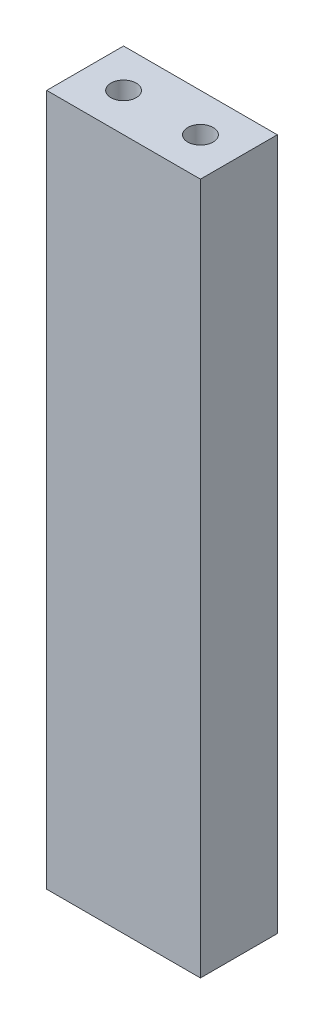
SolidWorks part; units mm, degrees
ref_plane "Front Plane" through (0, 0, 0) normal (0, 0, 1) x (1, 0, 0)
ref_plane "Top Plane" through (0, 0, 0) normal (0, 1, 0) x (1, 0, 0)
ref_plane "Right Plane" through (0, 0, 0) normal (1, 0, 0) x (0, 0, -1)
sketch "Sketch1" plane through (0, 0, 0) normal (0, 1, 0) x (1, 0, 0)
  line L1 (-10, -5) -> (10, -5)
  line L2 (-10, -5) -> (-10, 5)
  line L3 (-10, 5) -> (10, 5)
  line L4 (10, -5) -> (10, 5)
  line L5 (-10, -5) -> (10, 5) construction
  line L6 (-10, 5) -> (10, -5) construction
  point P0 (0, 0)
  dimension "D1" = 20
  dimension "D2" = 10
extrude "Boss-Extrude1" add sketch "Sketch1" along normal blind 90
hole_wizard "M4x0.7 Tapped Hole1" positions "Sketch2" profile "Sketch4" tap size "M4x0.7" standard "ANSI Metric"
sketch "Sketch2" plane through (0, 0, 0) normal (0, -1, 0) x (-1, 0, 0)
  line L0 (-5, 0) -> (5, 0)
  point P1 (-5, 0)
  point P2 (5, 0)
  point P4 (0, 0)
  dimension "D1" = 10
sketch "Sketch4" plane through (5, 0, 0) normal (1, 0, 0) x (0, 0, -1)
  line L0 (0, 0) -> (0, 15.9914)
  line L1 (0, 15.9914) -> (1.65, 15)
  line L2 (1.65, 15) -> (1.65, 0)
  line L5 (1.65, 0) -> (0, 0)
  line L10 (0, 15.9914) -> (-1.65, 15) construction
  line L11 (0, -6.35) -> (0, 107.95) construction
  dimension "Tap Drill Dia." = 3.3
  dimension "Tap Drill Depth" = 15
  dimension "Drill Angle" = 118
cosmetic thread "Hole Thread1" parameters "D1"=15, "D2"=4
cosmetic thread "Hole Thread2" parameters "D1"=15, "D2"=4
hole_wizard "M4x0.7 Tapped Hole2" positions "Sketch5" profile "Sketch6" tap size "M4x0.7" standard "ANSI Metric"
sketch "Sketch5" plane through (0, 90, 0) normal (0, 1, 0) x (1, 0, 0)
  line L0 (-5, 0) -> (5, 0)
  point P1 (-5, 0)
  point P2 (5, 0)
  point P5 (0, 0)
  dimension "D1" = 10
sketch "Sketch6" plane through (-5, 90, 0) normal (1, 0, 0) x (0, 0, 1)
  line L0 (0, 0) -> (0, 15.9914)
  line L1 (0, 15.9914) -> (1.65, 15)
  line L2 (1.65, 15) -> (1.65, 0)
  line L5 (1.65, 0) -> (0, 0)
  line L10 (0, 15.9914) -> (-1.65, 15) construction
  line L11 (0, -6.35) -> (0, 107.95) construction
  dimension "Tap Drill Dia." = 3.3
  dimension "Tap Drill Depth" = 15
  dimension "Drill Angle" = 118
cosmetic thread "Hole Thread3" parameters "D1"=14.3, "D2"=4
cosmetic thread "Hole Thread4" parameters "D1"=14.3, "D2"=4
